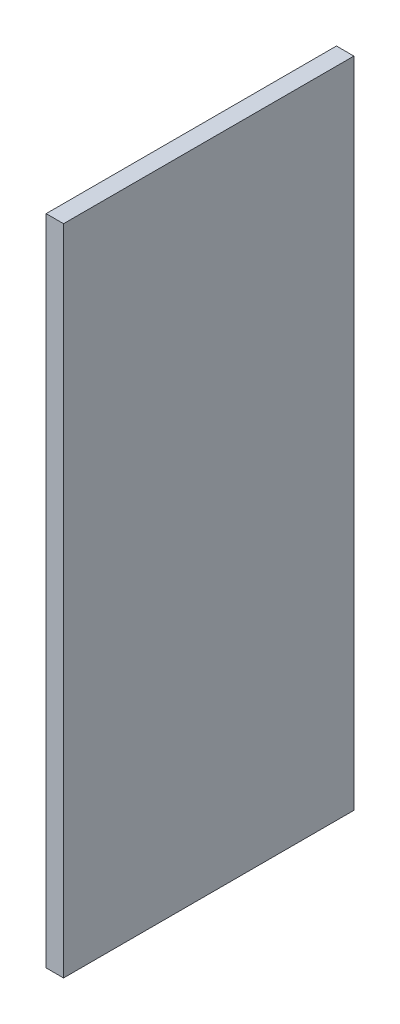
SolidWorks part; units mm, degrees
material "PVC 0.007 Plasticized"
ref_plane "Front Plane" through (0, 0, 0) normal (0, 0, 1) x (1, 0, 0)
ref_plane "Top Plane" through (0, 0, 0) normal (0, 1, 0) x (1, 0, 0)
ref_plane "Right Plane" through (0, 0, 0) normal (1, 0, 0) x (0, 0, -1)
sketch "Sketch1" plane through (0, 0, 0) normal (0, 0, 1) x (1, 0, 0)
  line L0 (0, 0) -> (0, 57.15)
  dimension "D1" = 57.15
surface "Surface-Extrude1" sketch "Sketch1" parameters "D1"=25.4
thicken "Thicken1" surfaces to thicken 101 thickness 0.762 thickness side both sides parameters "D1"=0.762
